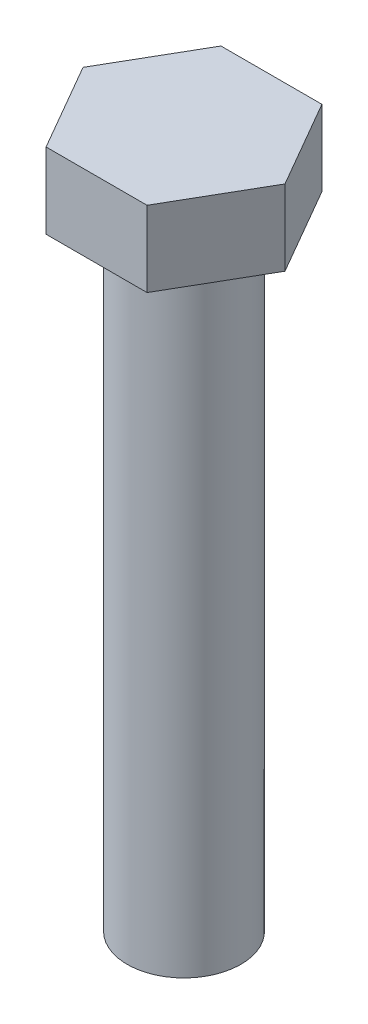
SolidWorks part; units mm, degrees
material "Cast Stainless Steel"
ref_plane "Front Plane" through (0, 0, 0) normal (0, 0, 1) x (1, 0, 0)
ref_plane "Top Plane" through (0, 0, 0) normal (0, 1, 0) x (1, 0, 0)
ref_plane "Right Plane" through (0, 0, 0) normal (1, 0, 0) x (0, 0, -1)
sketch "Sketch1" plane through (0, 0, 0) normal (0, 1, 0) x (1, 0, 0)
  line L1 (8.2416, 0) -> (4.1208, 7.1374)
  line L2 (4.1208, 7.1374) -> (-4.1208, 7.1374)
  line L3 (-4.1208, 7.1374) -> (-8.2416, 0)
  line L4 (-8.2416, 0) -> (-4.1208, -7.1374)
  line L5 (-4.1208, -7.1374) -> (4.1208, -7.1374)
  line L6 (4.1208, -7.1374) -> (8.2416, 0)
  circle A0 centre (0, 0) radius 7.1374 construction
  dimension "D1" = 14.2748
extrude "Boss-Extrude1" add sketch "Sketch1" along normal blind 6.1722
sketch "Sketch2" plane through (0, 0, 0) normal (0, -1, 0) x (1, 0, 0)
  circle A0 centre (0, 0) radius 4.6437
  dimension "D1" = 9.2874
extrude "Boss-Extrude2" add sketch "Sketch2" along normal blind 50.8
